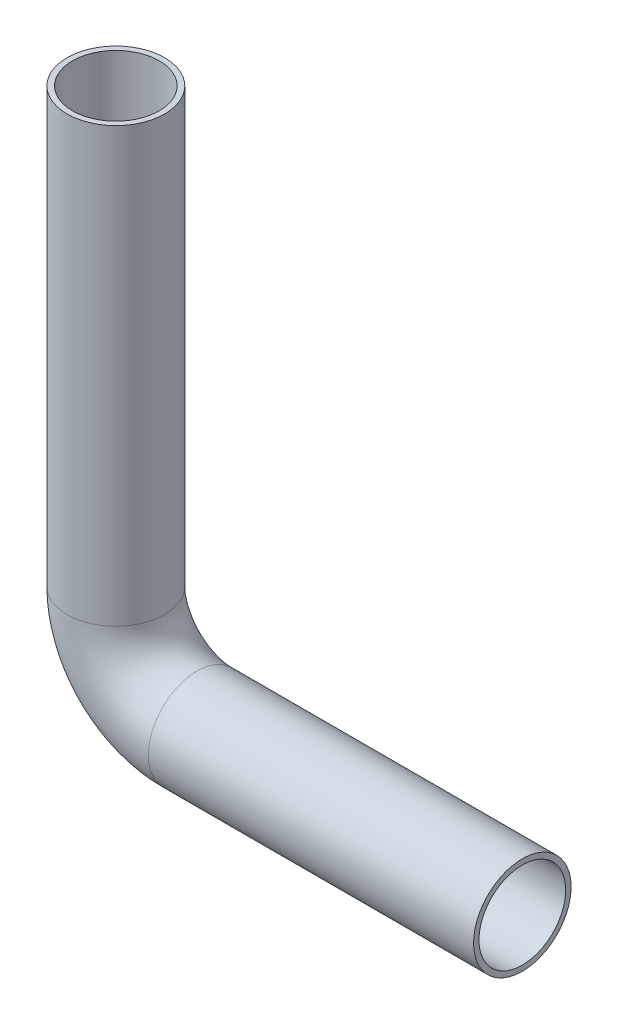
SolidWorks part; units mm, degrees
material "Nickel"
ref_plane "Front Plane" through (0, 0, 0) normal (0, 0, 1) x (1, 0, 0)
ref_plane "Top Plane" through (0, 0, 0) normal (0, 1, 0) x (1, 0, 0)
ref_plane "Right Plane" through (0, 0, 0) normal (1, 0, 0) x (0, 0, -1)
sketch "Sketch1" plane through (0, 0, 0) normal (0, 0, 1) x (1, 0, 0)
  line L0 (-102.1144, 38.661) -> (-102.1144, -41.339)
  line L1 (-87.1144, -56.339) -> (-27.1144, -56.339)
  arc A0 (-102.1144, -41.339) -> (-87.1144, -56.339) centre (-87.1144, -41.339) ccw
  dimension "D1" = 15
  dimension "D2" = 80
  dimension "D3" = 60
ref_plane "Plane1" through (0, 38.661, 0) normal (0, 1, 0) x (1, 0, 0)
sketch "Sketch2" plane through (0, 38.661, 0) normal (0, 1, 0) x (1, 0, 0)
  line L0 (-102.1144, 0) -> (-87.1144, 0) construction
  line L1 (0, 0) -> (-102.1144, 0) construction
  circle A0 centre (-102.1144, 0) radius 9
  dimension "D1" = 18
  dimension "D2" = 102.1144
sweep "Sweep1" add profiles "Sketch2" path "Sketch1"
shell "Shell1" thickness 1
